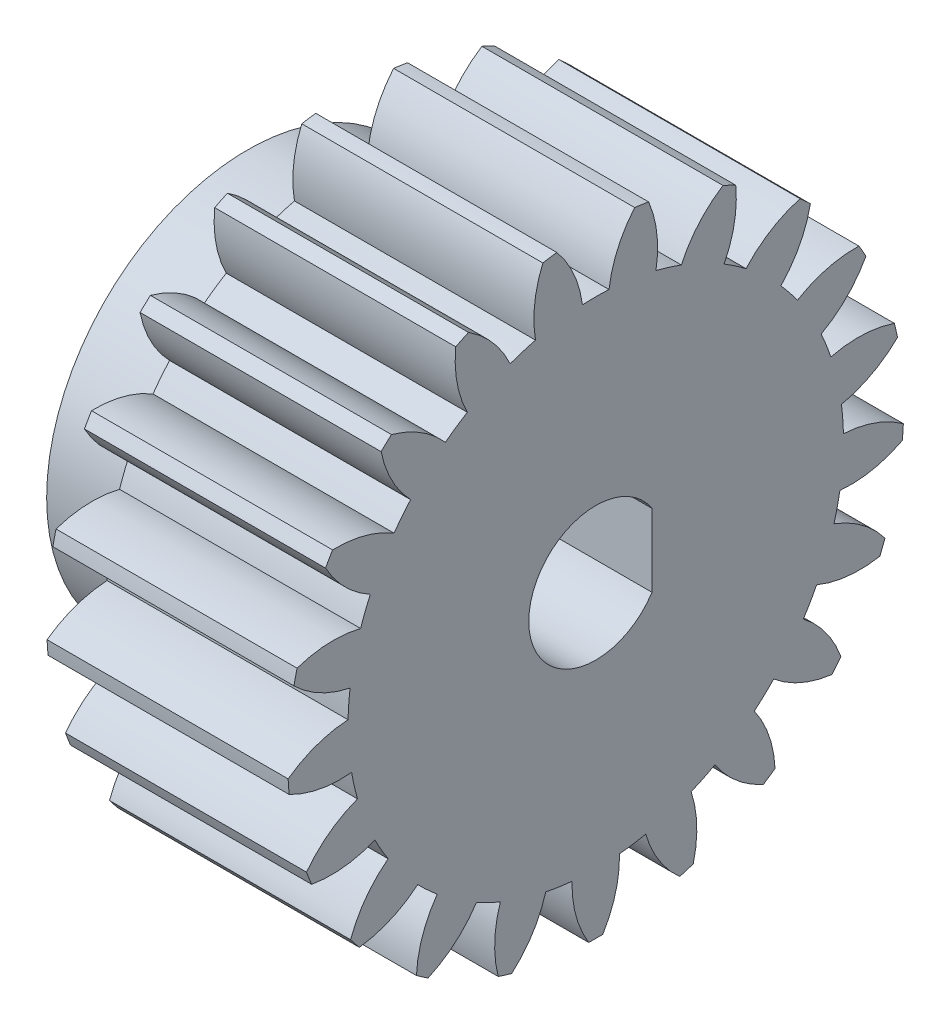
SolidWorks part; units mm, degrees
ref_plane "Plane1" through (0, 0, 0) normal (0, 0, 1) x (1, 0, 0)
ref_plane "Plane2" through (0, 0, 0) normal (0, 1, 0) x (1, 0, 0)
ref_plane "Plane3" through (0, 0, 0) normal (1, 0, 0) x (0, 0, -1)
other "Configuration Table"
sketch "HoldingSke" plane through (0, 0, 0) normal (0, 1, 0) x (1, 0, 0)
  line L0 (0, 0) -> (0.9336, -0.3584)
  line L1 (-15, 0) -> (100, 0) construction
  line L2 (0, 0) -> (-2.1039, 2.3779)
  line L3 (0, 0) -> (-11.863, 4.5341)
  line L4 (0, 0) -> (8.0624, 3.0949)
  line L5 (0, 0) -> (-46.8476, -17.4728)
  line L6 (0, 0) -> (-7.4607, -5.0337)
  line L7 (-2.1039, 2.3779) -> (8.6586, 51.2059)
  line L8 (-76.2, 54.61) -> (-75.3, 54.61)
  line L9 (-71.009, 38.7566) -> (-53.1078, 45.2721)
  line L10 (-76.2, 71.12) -> (104.1128, 71.12)
  line L11 (0, 0) -> (-9, 0)
  line L12 (-76.2, 101.6) -> (-76.162, 101.6)
  line L13 (24.9733, 27.94) -> (52.9518, 28.4284)
  line L14 (24.9733, 27.94) -> (24.9743, 27.94)
  line L15 (24.9733, 27.94) -> (100.4006, 29.5858)
  line L16 (-63.627, -1) -> (-12.827, -1)
  circle A0 centre (0, 0) radius 2.5
  circle A1 centre (0, 0) radius 9.249
  circle A2 centre (0, 0) radius 37.5
  circle A3 centre (0, 0) radius 2.5
  dimension "MHD" = 18.498
  dimension "Hub_dia" = 75
  dimension "Bore" = 5
  dimension "MBD" = 5
  dimension "Num_teeth" = 21
  dimension "Pitch" = 1
  dimension "Overall_len" = 50
  dimension "Show_teeth" = 21
  dimension "Thickness" = 9
  dimension "OAL" = 50.0001
  dimension "T_dim" = 0.9
  dimension "Ap" = 20
  dimension "H" = 19.05
  dimension "Pitch_radius" = 180.3128
  dimension "Width" = 9
  dimension "Backlash" = 0.038
  dimension "Addendum_fac" = 1
  dimension "Dedendum_fac" = 1.25
  dimension "Clearance_fac" = 0.25
  dimension "Dedendum_add" = 0.001
  dimension "Module" = 1
sketch "BasProSke" plane through (0, 0, 0) normal (0, 1, 0) x (1, 0, 0)
  line L0 (-10, 0) -> (60, 0) construction
  line L1 (0, 0) -> (0, 11.5)
  line L2 (0, 0) -> (9, 0)
  line L3 (9, 0) -> (9, 11.5)
  line L4 (9, 11.5) -> (0, 11.5)
  dimension "Thickness" = 9
  dimension "Diameter" = 23
revolve "Base-Revolve" add sketch "BasProSke" angle 360 about L0
sketch "TooCutSke" plane through (0, 0, 0) normal (1, 0, 0) x (0, 0, -1)
  line L1 (0, 0) -> (0, 107) construction
  line L2 (0, 0) -> (-0.8511, 10.4654) construction
  line L3 (0, 0) -> (-3.1226, 20.7168) construction
  line L4 (-0.8511, 10.4654) -> (-1.5613, 10.3584) construction
  arc A0 (0.4953, 9.2357) -> (-0.4953, 9.2357) centre (0, 0) ccw
  arc A1 (1.4725, 11.431) -> (-1.4725, 11.431) centre (0, 0) ccw
  circle A2 centre (0, 0) radius 10.5 construction
  circle A3 centre (0, 0) radius 9.8668 construction
  arc A4 (-0.4953, 9.2357) -> (-1.4725, 11.431) centre (-4.6605, 8.6967) ccw
  arc A5 (1.4725, 11.431) -> (0.4953, 9.2357) centre (4.6605, 8.6967) ccw
  dimension "Root_dia" = 18.498
  dimension "Overcut_dia" = 23.0508
  dimension "Pitch_dia" = 21
  dimension "Base_dia" = 19.7335
  dimension "Flank_rad" = 4.2
  dimension "Half_ang" = 8.571
  dimension "Half_CT" = 0.7182
extrude "ToothCut" cut sketch "TooCutSke" along normal through all
fillet "Breaks" [suppressed] radius 0.02
fillet "RootFillets" [suppressed] radius 0.251
pattern_circular "TeethCuts" count 21 every 17.143 about axis through (-10, 0, 0) along (1, 0, 0) of "ToothCut", "RootFillets", "Breaks"
sketch "HubNeaOneSke" plane through (0, 0, 0) normal (-1, 0, 0) x (0, 0, 1)
  circle A0 centre (0, 0) radius 9.249
  dimension "Diameter" = 18.498
extrude "HubNearOne" [suppressed] add sketch "HubNeaOneSke" along normal blind 41.0001
sketch "HubNeaBotSke" plane through (0, 0, 0) normal (-1, 0, 0) x (0, 0, 1)
  circle A0 centre (0, 0) radius 9.249
  dimension "Diameter" = 18.498
extrude "HubNearBoth" [suppressed] add sketch "HubNeaBotSke" along normal blind 20.5
ref_plane "FarPln" through (9, 0, 0) normal (1, 0, 0) x (0, 0, -1)
sketch "HubFarSke" plane through (9, 0, 0) normal (1, 0, 0) x (0, 0, -1)
  circle A0 centre (0, 0) radius 9.249
  dimension "Diameter" = 18.498
extrude "HubFar" [suppressed] add sketch "HubFarSke" along normal blind 20.5
sketch "BorSke" plane through (0, 0, 0) normal (1, 0, 0) x (0, 0, -1)
  circle A0 centre (0, 0) radius 2.5
  dimension "Diameter" = 5
extrude "Bore" cut sketch "BorSke" along normal mid plane 100.0001
sketch "KeySke" plane through (0, 0, 0) normal (1, 0, 0) x (0, 0, -1)
  line L0 (-1, 0) -> (-1, 3.4)
  line L1 (-1, 3.4) -> (1, 3.4)
  line L2 (1, 3.4) -> (1, 0)
  line L3 (0, 0) -> (0, 34) construction
  line L4 (-1, 0) -> (1, 0)
  dimension "Offset" = 3.4
  dimension "Width" = 2
extrude "Keyway" [suppressed] cut sketch "KeySke" along normal mid plane 100.0001
pattern_circular "Keyway2" [suppressed] count 2 every 90 about axis through (-10, 0, 0) along (1, 0, 0)
sketch "Sketch1" plane through (0, 0, 0) normal (-1, 0, 0) x (0, 0, 1)
  circle A0 centre (0, 0) radius 7.5
  circle A1 centre (0, 0) radius 2.5
  dimension "D1" = 15
  dimension "D2" = 5
extrude "Boss-Extrude1" add sketch "Sketch1" along normal blind 4
sketch "Sketch2" plane through (-4, 0, 0) normal (-1, 0, 0) x (0, 0, 1)
  line L0 (-2.1, 1.3565) -> (-2.1, -1.3565)
  line L1 (2.5, 3.6508) -> (2.5, -4.3193) construction
  circle A0 centre (0, 0) radius 2.5
  circle M5 centre (0, 0) radius 2.5
  dimension "D1" = 5
  dimension "D2" = 4.6
extrude "Boss-Extrude2" add sketch "Sketch2" against normal through all contours L0 M5
equation "' \"Module@HoldingSke\" = 6.35"
equation "' \"Num_teeth@HoldingSke\" = 12"
equation "' \"Ap@HoldingSke\" =  20"
equation "' \"Ap@HoldingSke\" = 20"
equation "' \"Width@HoldingSke\" = 0.5 * 25.4"
equation "' \"Hub_dia@HoldingSke\"= 1 * 25.4"
equation "' \"Hub_dia@HoldingSke\" = 1 * 25.4"
equation "' \"Overall_len@HoldingSke\" = 1.0 * 25.4"
equation "' \"Bore@HoldingSke\" = 0.75 * 25.4"
equation "' \"T_dim@HoldingSke\" = 0.1 * 25.4"
equation "' \"Width@KeySke\" = 0.25 * 25.4"
equation "' \"Show_teeth@HoldingSke\" = 13"
equation "' \"Backlash@HoldingSke\" = 0.009 * 25.4"
equation "' \"Addendum_fac@HoldingSke\" = 1.0"
equation "' \"Dedendum_fac@HoldingSke\" = 1.25"
equation "' \"Dedendum_add@HoldingSke\" = 0.00005 * 25.4"
equation "' \"Clearance_fac@HoldingSke\" = 0.25"
equation "\"Pitch@HoldingSke\" = 1 / \"Module@HoldingSke\""
equation "\"Overcut_dia@TooCutSke\" = (\"Num_teeth@HoldingSke\" + 2 * \"Addendum_fac@HoldingSke\") / \"Pitch@HoldingSke\" + 0.002 * 25.4"
equation "\"Pitch_dia@TooCutSke\" = \"Num_teeth@HoldingSke\" / \"Pitch@HoldingSke\""
equation "\"Base_dia@TooCutSke\" = \"Num_teeth@HoldingSke\" / \"Pitch@HoldingSke\" * cos((\"Ap@HoldingSke\"  * 3.14159265 / 180))"
equation "\"Root_dia@TooCutSke\" = (\"Num_teeth@HoldingSke\" + 2) / \"Pitch@HoldingSke\" - 2 * (\"Addendum_fac@HoldingSke\" + \"Dedendum_fac@HoldingSke\") / \"Pitch@HoldingSke\" - \"Dedendum_add@HoldingSke\" * 2"
equation "\"Half_ang@TooCutSke\" = 180 / \"Num_teeth@HoldingSke\""
equation "\"Half_CT@TooCutSke\" = \"Num_teeth@HoldingSke\" / \"Pitch@HoldingSke\" * sin((3.14159265 / 2 / \"Num_teeth@HoldingSke\")) / 2 - 7 * \"Backlash@HoldingSke\" / 4"
equation "\"Flank_rad@TooCutSke\" = \"Num_teeth@HoldingSke\" / \"Pitch@HoldingSke\" / 5"
equation "\"Radius@RootFillets\" = \"Clearance_fac@HoldingSke\" / \"Pitch@HoldingSke\" + \"Dedendum_add@HoldingSke\""
equation "\"Break_rad@Breaks\" = 0.02 / \"Pitch@HoldingSke\""
equation "\"Thickness@HoldingSke\" = \"Width@HoldingSke\""
equation "\"OAL@HoldingSke\" = \"Thickness@HoldingSke\""
equation "\"MHD@HoldingSke\" = (\"Num_teeth@HoldingSke\" + 2) / \"Pitch@HoldingSke\" - 2 * (\"Addendum_fac@HoldingSke\" + \"Dedendum_fac@HoldingSke\")  / \"Pitch@HoldingSke\" - \"Dedendum_add@HoldingSke\" * 2"
equation "\"MBD@HoldingSke\" = (\"Num_teeth@HoldingSke\" + 2) / \"Pitch@HoldingSke\" - 2 * (\"Addendum_fac@HoldingSke\" + \"Dedendum_fac@HoldingSke\")  / \"Pitch@HoldingSke\" - \"Dedendum_add@HoldingSke\" * 2 - 0.002 * 25.4"
equation "\"MHD@HoldingSke\" = ((sgn( \"MHD@HoldingSke\" - \"Hub_dia@HoldingSke\" )-1)*( \"MHD@HoldingSke\" - \"Hub_dia@HoldingSke\" ))/-2+ \"Hub_dia@HoldingSke\""
equation "\"MBD@HoldingSke\" = ((sgn( \"MBD@HoldingSke\" - \"Bore@HoldingSke\" )-1)*( \"MBD@HoldingSke\" - \"Bore@HoldingSke\" ))/-2+ \"Bore@HoldingSke\""
equation "\"OAL@HoldingSke\" = ((sgn( \"OAL@HoldingSke\" - \"Overall_len@HoldingSke\" )+1)*( \"OAL@HoldingSke\" - \"Overall_len@HoldingSke\" ))/2 + \"Overall_len@HoldingSke\" + 0.000002 * 25.4"
equation "\"Num_teeth@TeethCuts\" = int( \"Show_teeth@HoldingSke\" ) + 1"
equation "\"Num_teeth@TeethCuts\" = ((sgn( \"Num_teeth@TeethCuts\" - \"Num_teeth@HoldingSke\" )-1)*( \"Num_teeth@TeethCuts\" - \"Num_teeth@HoldingSke\" ))/-2+ \"Num_teeth@HoldingSke\""
equation "\"Num_teeth@TeethCuts\" = ((sgn( \"Num_teeth@TeethCuts\" - 2.0)+1)*( \"Num_teeth@TeethCuts\" - 2.0))/2 +2.0"
equation "\"Angle@TeethCuts\" = 360.0 / \"Num_teeth@HoldingSke\""
equation "\"Diameter@BasProSke\" = (\"Num_teeth@HoldingSke\" + 2 * \"Addendum_fac@HoldingSke\") / \"Pitch@HoldingSke\""
equation "\"Thickness@BasProSke\"  = \"Thickness@HoldingSke\""
equation "' \"Fillet_rad@BasProSke\" =  \"Thickness@HoldingSke\" * 0.05"
equation "' \"Fillet_rad@BasProSke\" = \"Thickness@HoldingSke\" * 0.05"
equation "\"MHD@HoldingSke\" = ((sgn( \"MHD@HoldingSke\" - \"Root_dia@TooCutSke\" )-1)*( \"MHD@HoldingSke\" - \"Root_dia@TooCutSke\" ))/-2+ \"Root_dia@TooCutSke\""
equation "\"Diameter@HubNeaOneSke\" = \"MHD@HoldingSke\""
equation "\"Length@HubNearOne\" = \"OAL@HoldingSke\" - \"Thickness@BasProSke\""
equation "\"Diameter@HubNeaBotSke\" = \"MHD@HoldingSke\""
equation "\"Length@HubNearBoth\" = ( \"OAL@HoldingSke\" - \"Thickness@BasProSke\" ) / 2.0"
equation "\"Thickness@FarPln\" = \"Thickness@BasProSke\""
equation "\"Diameter@HubFarSke\" = \"MHD@HoldingSke\""
equation "\"Length@HubFar\" = ( \"OAL@HoldingSke\" - \"Thickness@BasProSke\" ) / 2.0"
equation "\"Diameter@BorSke\" = \"MBD@HoldingSke\""
equation "\"D1@Bore\" = \"OAL@HoldingSke\" * 2.0"
equation "\"D1@Keyway\" = \"OAL@HoldingSke\" * 2.0"
equation "\"Offset@KeySke\" = \"T_dim@HoldingSke\" + \"MBD@HoldingSke\" / 2.0"
